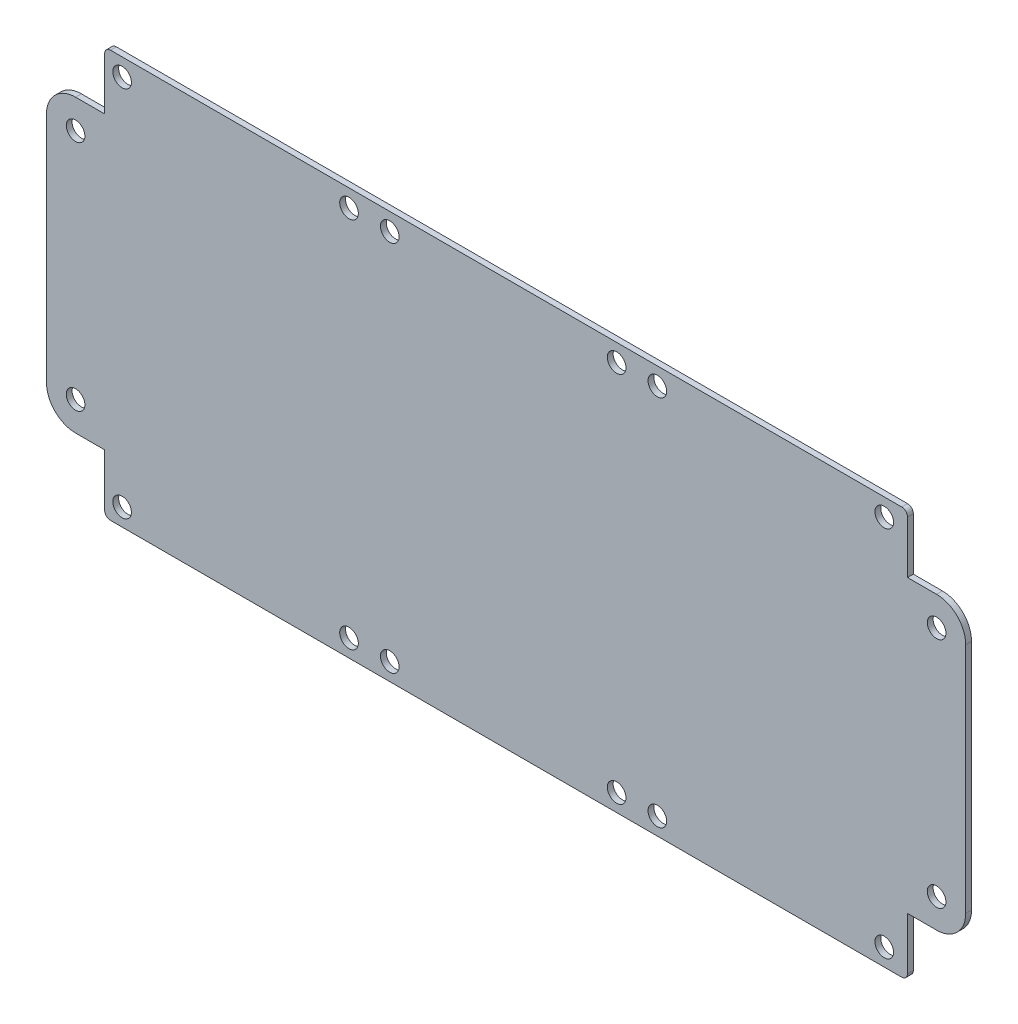
SolidWorks part; units mm, degrees
ref_plane "Front Plane" through (0, 0, 0) normal (0, 0, 1) x (1, 0, 0)
ref_plane "Top Plane" through (0, 0, 0) normal (0, 1, 0) x (1, 0, 0)
ref_plane "Right Plane" through (0, 0, 0) normal (1, 0, 0) x (0, 0, -1)
sketch "Sketch1" plane through (0, 0, 0) normal (0, 0, 1) x (1, 0, 0)
  line L0 (110.0857, -21.015) -> (110.0857, -30.015)
  line L1 (-26.9143, 38.985) -> (109.0857, 38.985)
  line L2 (-27.9143, 37.985) -> (-27.9143, 28.985)
  line L3 (-26.9143, -31.015) -> (109.0857, -31.015)
  line L4 (110.0857, 37.985) -> (110.0857, 28.985)
  line L7 (110.0857, 28.985) -> (115.0857, 28.985)
  line L9 (110.0857, -21.015) -> (115.0857, -21.015)
  line L10 (-27.9143, -21.015) -> (-27.9143, -30.015)
  line L11 (120.0857, 23.985) -> (120.0857, -16.015)
  line L12 (-27.9143, 28.985) -> (-32.9143, 28.985)
  line L14 (-27.9143, -21.015) -> (-32.9143, -21.015)
  line L15 (-37.9143, 23.985) -> (-37.9143, -16.015)
  circle A0 centre (-24.9143, 35.985) radius 1.6
  circle A1 centre (14.0857, 35.985) radius 1.6
  circle A2 centre (-24.9143, -28.015) radius 1.6
  circle A3 centre (14.0857, -28.015) radius 1.6
  circle A4 centre (21.0857, 35.985) radius 1.6
  circle A5 centre (60.0857, 35.985) radius 1.6
  circle A6 centre (60.0857, -28.015) radius 1.6
  circle A7 centre (21.0857, -28.015) radius 1.6
  circle A8 centre (67.0857, 35.985) radius 1.6
  circle A9 centre (106.0857, 35.985) radius 1.6
  circle A10 centre (106.0857, -28.015) radius 1.6
  circle A11 centre (67.0857, -28.015) radius 1.6
  arc A20 (115.0857, 28.985) -> (120.0857, 23.985) centre (115.0857, 23.985) cw
  arc A21 (115.0857, -21.015) -> (120.0857, -16.015) centre (115.0857, -16.015) ccw
  arc A22 (-32.9143, -21.015) -> (-37.9143, -16.015) centre (-32.9143, -16.015) cw
  arc A23 (-32.9143, 28.985) -> (-37.9143, 23.985) centre (-32.9143, 23.985) ccw
  circle A24 centre (-32.9143, -16.015) radius 1.6
  circle A25 centre (-32.9143, 23.985) radius 1.6
  circle A26 centre (115.0857, 23.985) radius 1.6
  circle A27 centre (115.0857, -16.015) radius 1.6
  arc A28 (109.0857, -31.015) -> (110.0857, -30.015) centre (109.0857, -30.015) ccw
  arc A29 (109.0857, 38.985) -> (110.0857, 37.985) centre (109.0857, 37.985) cw
  arc A30 (-27.9143, -30.015) -> (-26.9143, -31.015) centre (-26.9143, -30.015) ccw
  arc A31 (-26.9143, 38.985) -> (-27.9143, 37.985) centre (-26.9143, 37.985) ccw
  dimension "D3" = 3
  dimension "D4" = 3
  dimension "D5" = 39
  dimension "D6" = 3
  dimension "D7" = 39
  dimension "D8" = 39
  dimension "D9" = 39
  dimension "D10" = 39
  dimension "D11" = 39
  dimension "D12" = 10
  dimension "D14" = 7
  dimension "D15" = 7
  dimension "D17" = 7
  dimension "D18" = 7
  dimension "D20" = 3
  dimension "D21" = 3
  dimension "D22" = 3
  dimension "D25" = 3
  dimension "D26" = 3
  dimension "D27" = 3
  dimension "D28" = 3
  dimension "D45" = 5
  dimension "D46" = 1
  dimension "D1" = 138
  dimension "D2" = 70
  dimension "D40" = 10
  dimension "D41" = 10
  dimension "D42" = 10
  dimension "D43" = 10
  dimension "D44" = 10
extrude "Boss-Extrude1" add sketch "Sketch1" along normal blind 1
